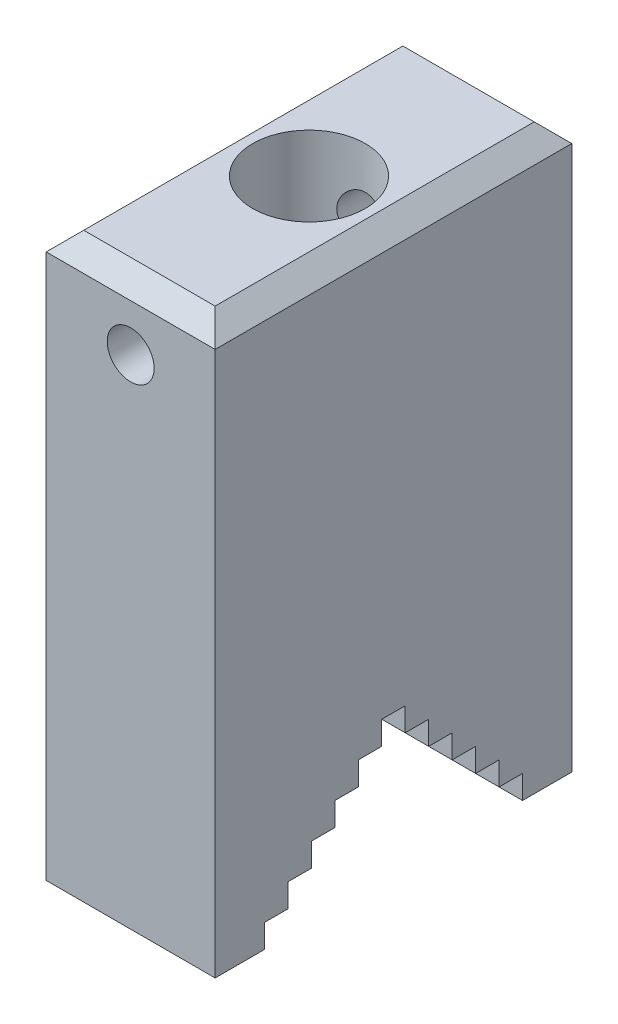
SolidWorks part; units mm, degrees
ref_plane "Front Plane" through (0, 0, 0) normal (0, 0, 1) x (1, 0, 0)
ref_plane "Top Plane" through (0, 0, 0) normal (0, 1, 0) x (1, 0, 0)
ref_plane "Right Plane" through (0, 0, 0) normal (1, 0, 0) x (0, 0, -1)
sketch "Sketch1" plane through (0, 0, 0) normal (1, 0, 0) x (0, 0, -1)
  line L0 (0, 0) -> (0, 50000) construction
  line L1 (-19, 60) -> (19, 60)
  line L2 (-19, 60) -> (-19, 0)
  line L3 (-19, 0) -> (19, 0)
  line L4 (19, 60) -> (19, 0)
  line L5 (-19, 60) -> (19, 0) construction
  line L6 (-19, 0) -> (19, 60) construction
  line L7 (-13.75, 0) -> (-13.75, 2.5)
  line L8 (-13.75, 2.5) -> (-11.25, 2.5)
  line L9 (-11.25, 2.5) -> (-11.25, 5)
  line L10 (-11.25, 5) -> (-8.75, 5)
  line L11 (-8.75, 5) -> (-8.75, 7.5)
  line L12 (-8.75, 7.5) -> (-6.25, 7.5)
  line L13 (-6.25, 7.5) -> (-6.25, 10)
  line L14 (-6.25, 10) -> (-3.75, 10)
  line L15 (-3.75, 10) -> (-3.75, 12.5)
  line L16 (-3.75, 12.5) -> (-1.25, 12.5)
  line L17 (-1.25, 12.5) -> (-1.25, 15)
  line L18 (1.25, 12.5) -> (1.25, 15)
  line L19 (3.75, 12.5) -> (1.25, 12.5)
  line L20 (3.75, 10) -> (3.75, 12.5)
  line L21 (6.25, 10) -> (3.75, 10)
  line L22 (6.25, 7.5) -> (6.25, 10)
  line L23 (8.75, 7.5) -> (6.25, 7.5)
  line L24 (8.75, 5) -> (8.75, 7.5)
  line L25 (11.25, 5) -> (8.75, 5)
  line L26 (11.25, 2.5) -> (11.25, 5)
  line L27 (13.75, 2.5) -> (11.25, 2.5)
  line L28 (13.75, 0) -> (13.75, 2.5)
  line L29 (-1.25, 15) -> (1.25, 15)
  point P0 (0, 30)
  point P5 (0, 0)
  dimension "D1" = 38
  dimension "D2" = 60
  dimension "D3" = 2.5
  dimension "D4" = 27.5
extrude "Boss-Extrude1" add sketch "Sketch1" along normal mid plane 18 contours L17 L29 L18 L19 L20 L21 L22 L23 L24 L25 L26 L27 L28 L3 L4 L1 L2 L7 L8 L9 L10 L11 L12 L13 L14 L15 L16
chamfer "Chamfer1" distance 2 angle 45 4 edges at (0, 60, -19) (-9, 60, 0) (0, 60, 19) (9, 60, 0)
hole_wizard "Ø12.0mm Dowel Hole1" positions "Sketch2" profile "Sketch3" hole size "Ø12.0" standard "ISO"
sketch "Sketch2" plane through (0, 60, 0) normal (0, 1, 0) x (1, 0, 0)
  point P0 (0, 0)
sketch "Sketch3" plane through (0, 60, 0) normal (1, 0, 0) x (0, 0, 1)
  line L0 (0, 0) -> (0, 21.4641)
  line L1 (0, 21.4641) -> (6, 18)
  line L2 (6, 18) -> (6, 0)
  line L5 (6, 0) -> (0, 0)
  line L10 (0, 21.4641) -> (-6, 18) construction
  line L11 (0, -6.35) -> (0, 107.95) construction
  dimension "Hole Dia." = 12
  dimension "Hole Depth" = 18
  dimension "Drill Angle" = 120
hole_wizard "M6x1.0 Tapped Hole1" positions "Sketch4" profile "Sketch5" tap size "M6x1.0" standard "ANSI Metric" end condition through all
sketch "Sketch4" plane through (0, 0, 19) normal (0, 0, 1) x (1, 0, 0)
  line L0 (-7, 60) -> (7, 60) construction
  point P0 (0, 53)
  point P5 (0, 0)
  dimension "D1" = 7
sketch "Sketch5" plane through (0, 53, 19) normal (1, 0, 0) x (0, -1, 0)
  line L0 (0, 0) -> (0, 38)
  line L1 (0, 38) -> (2.5, 38)
  line L2 (2.5, 38) -> (2.5, 0)
  line L5 (2.5, 0) -> (0, 0)
  line L11 (0, -6.35) -> (0, 107.95) construction
  dimension "Thru Tap Drill Dia." = 5
  dimension "Thru Tap Drill Depth" = 38
cosmetic thread "Hole Thread1" parameters "D2"=6
